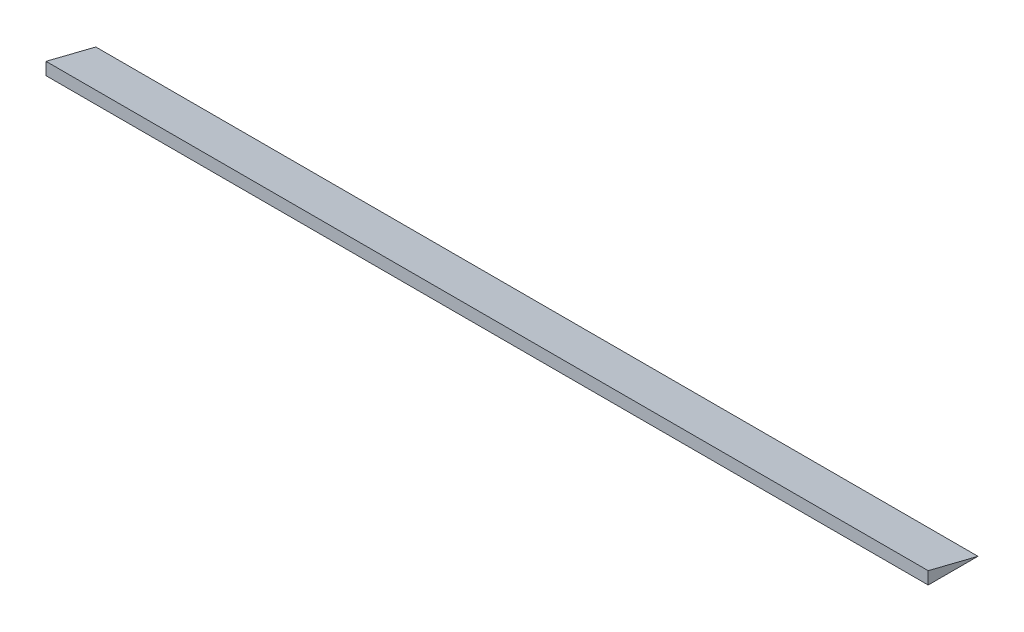
SolidWorks part; units mm, degrees
material "Balsa"
ref_plane "Front Plane" through (0, 0, 0) normal (0, 0, 1) x (1, 0, 0)
ref_plane "Top Plane" through (0, 0, 0) normal (0, 1, 0) x (1, 0, 0)
ref_plane "Right Plane" through (0, 0, 0) normal (1, 0, 0) x (0, 0, -1)
sketch "Sketch1" plane through (0, 0, 0) normal (1, 0, 0) x (0, 0, -1)
  line L0 (0, 0) -> (38.1, 0)
  line L1 (38.1, 0) -> (0, 9.525)
  line L2 (0, 9.525) -> (0, 0)
  dimension "D1" = 38.1
  dimension "D2" = 9.525
extrude "Boss-Extrude1" add sketch "Sketch1" along normal blind 675
